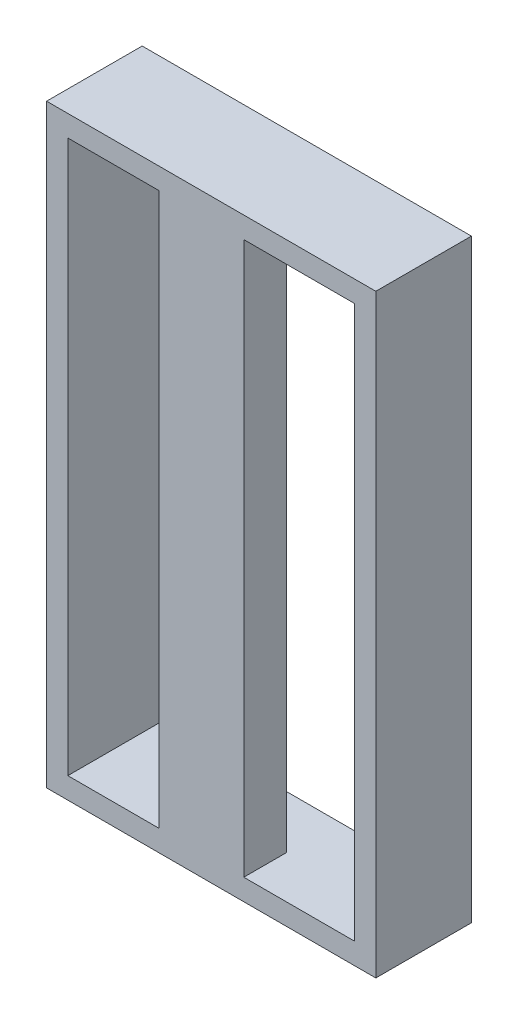
SolidWorks part; units mm, degrees
ref_plane "Front Plane" through (0, 0, 0) normal (1, 0, 0) x (0, 1, 0)
ref_plane "Top Plane" through (0, 0, 0) normal (0, 0, 1) x (0, 1, 0)
ref_plane "Right Plane" through (0, 0, 0) normal (0, 1, 0) x (-1, 0, 0)
sketch "Sketch1" plane through (0, 0, 0) normal (0, 0, 1) x (0, 1, 0)
  line L1 (0, 0) -> (56, 0)
  line L2 (0, 0) -> (0, 31)
  line L3 (0, 31) -> (56, 31)
  line L4 (56, 0) -> (56, 31)
  dimension "D1" = 31
  dimension "D2" = 56
extrude "Boss-Extrude1" add sketch "Sketch1" along normal blind 9
sketch "Sketch2" plane through (0, 0, 9) normal (0, 0, 1) x (1, 0, 0)
  line L8 (-29, 2) -> (-2, 2)
  line L9 (-2, 2) -> (-2, 54)
  line L10 (-2, 54) -> (-29, 54)
  line L11 (-29, 54) -> (-29, 2)
  line L12 (-29, 2) -> (-2, 2)
  line L13 (-2, 2) -> (-2, 54)
  line L14 (-2, 54) -> (-29, 54)
  line L15 (-29, 54) -> (-29, 2)
  dimension "D1" = 2
extrude "Cut-Extrude1" cut sketch "Sketch2" along direction (0, 0, -1) on the side against the normal through all
sketch "Sketch3" plane through (0, 0, 9) normal (0, 0, 1) x (1, 0, 0)
  line L0 (-2, 54) -> (-29, 54) construction
  line L1 (-12.4334, 54) -> (-20.4334, 54)
  line L2 (-12.4334, 54) -> (-12.4334, 2)
  line L3 (-12.4334, 2) -> (-20.4334, 2)
  line L4 (-20.4334, 54) -> (-20.4334, 2)
  line L5 (-29, 2) -> (-2, 2) construction
  dimension "D1" = 8
extrude "Boss-Extrude2" add sketch "Sketch3" against normal blind 4
